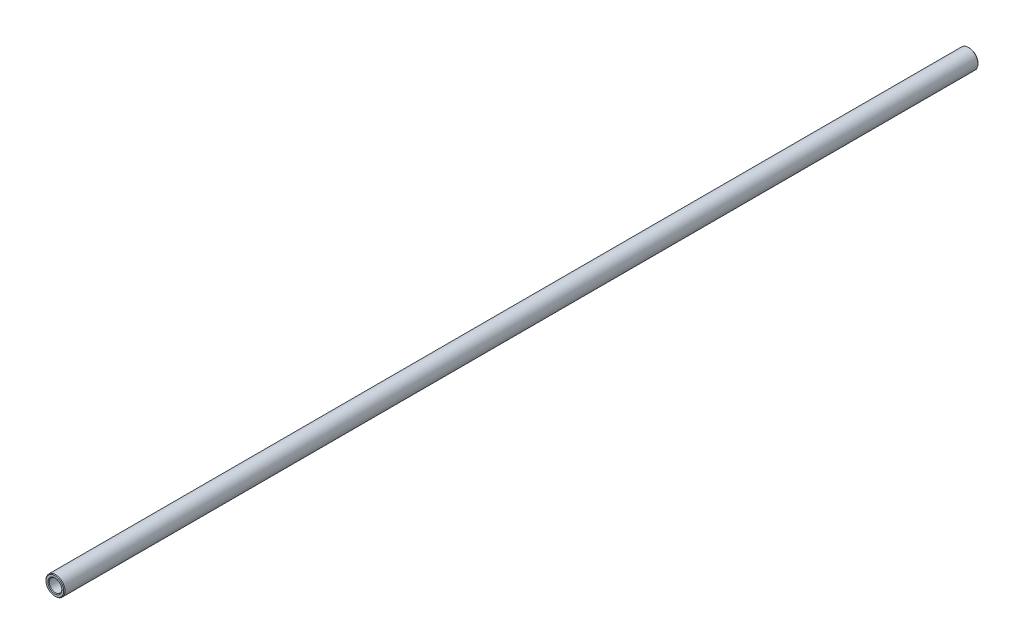
SolidWorks part; units mm, degrees
ref_plane "Front Plane" through (0, 0, 0) normal (0, 0, 1) x (1, 0, 0)
ref_plane "Top Plane" through (0, 0, 0) normal (0, 1, 0) x (1, 0, 0)
ref_plane "Right Plane" through (0, 0, 0) normal (1, 0, 0) x (0, 0, -1)
sketch "Sketch1" plane through (0, 0, 0) normal (0, 0, 1) x (1, 0, 0)
  circle A0 centre (0, 0) radius 3.175 construction
  circle A1 centre (0, 0) radius 2.1082 construction
  point P4 (0, 3.175)
  dimension "ID" = 4.2164
  dimension "OD" = 6.35
sketch "Sketch2" plane through (0, 0, 0) normal (1, 0, 0) x (0, 0, -1)
  line L0 (-152.4, 3.175) -> (152.4, 3.175) construction
  point P2 (144.4625, 3.175)
  point P3 (-144.4625, 3.175)
  dimension "Length" = 304.8
  dimension "D1" = 7.9375
  dimension "D2" = 7.9375
sketch "Sketch3" plane through (0, 0, 0) normal (0, 0, 1) x (1, 0, 0)
  circle A0 centre (0, 0) radius 2.1082 construction
  circle A1 centre (0, 0) radius 3.175 construction
  circle A2 centre (0, 0) radius 2.1082
  circle A3 centre (0, 0) radius 3.175
extrude "Boss-Extrude1" add sketch "Sketch3" against normal up to vertex (152.4 mm away) and the other way up to vertex (152.4 mm away) up to point (0, 3.175, -152.4) other way up to point (0, 3.175, 152.4)
chamfer "Chamfer1" distance 0.2134 angle 45 4 edges at (3.175, 0, 152.4) (3.175, 0, -152.4) (2.1082, 0, 152.4) (2.1082, 0, -152.4)
equation "\"D1@Chamfer1\"=(\"OD@Sketch1\"-\"ID@Sketch1\")*0.1"
equation "\"D1@Sketch2\"=\"OD@Sketch1\"*1.25"
equation "\"D2@Sketch2\"=\"D1@Sketch2\""
